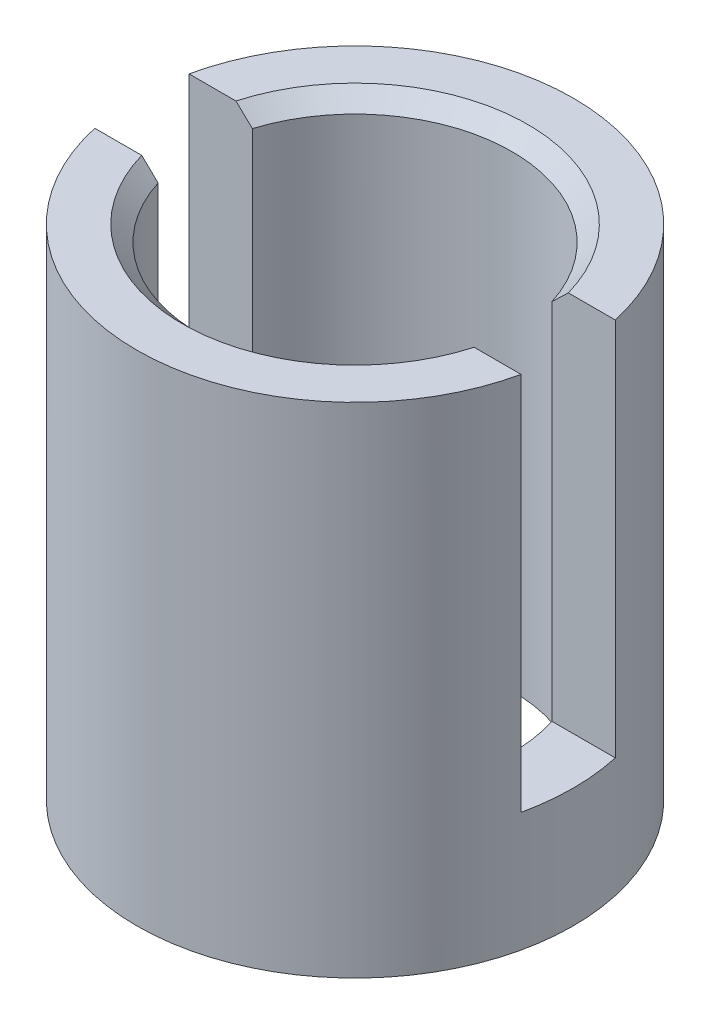
SolidWorks part; units mm, degrees
material "铸造碳钢"
ref_plane "前视基准面" through (0, 0, 0) normal (0, 0, 1) x (1, 0, 0)
ref_plane "上视基准面" through (0, 0, 0) normal (0, 1, 0) x (1, 0, 0)
ref_plane "右视基准面" through (0, 0, 0) normal (1, 0, 0) x (0, 0, -1)
sketch "草图1" plane through (0, 0, 0) normal (0, 1, 0) x (1, 0, 0)
  circle A0 centre (0, 0) radius 2
  circle A1 centre (0, 0) radius 2.78
  dimension "孔径" = 4
  dimension "外径" = 5.56
extrude "凸台-拉伸1" add sketch "草图1" along normal blind 6.35
sketch "草图2" plane through (0, 6.35, 0) normal (0, 1, 0) x (1, 0, 0)
  line L0 (-2.7145, 0.6) -> (2.7145, 0.6)
  line L1 (-2.78, 0) -> (2.78, 0) construction
  line L2 (-2.7145, -0.6) -> (2.7145, -0.6)
  circle A0 centre (0, 0) radius 2.78 construction
  arc A1 (-2.7145, 0.6) -> (-2.7145, -0.6) centre (0, 0) ccw
  arc A2 (2.7145, -0.6) -> (2.7145, 0.6) centre (0, 0) ccw
  dimension "槽宽" = 1.2
extrude "切除-拉伸1" cut sketch "草图2" against normal blind 4.83
chamfer "倒角1" distance 0.2 angle 45 3 edges at (0, 6.35, -2) (0, 6.35, 2) (0, 0, 2)
other "冻结***"
